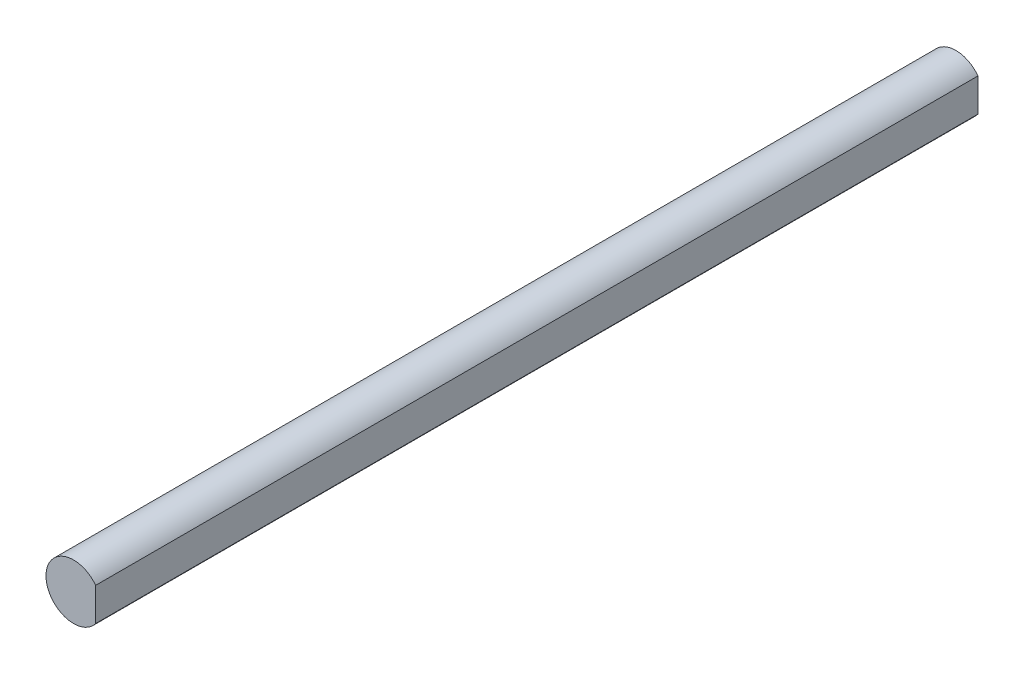
SolidWorks part; units mm, degrees
ref_plane "Plan de face" through (0, 0, 0) normal (0, 0, 1) x (1, 0, 0)
ref_plane "Plan de dessus" through (0, 0, 0) normal (0, 1, 0) x (1, 0, 0)
ref_plane "Plan de droite" through (0, 0, 0) normal (1, 0, 0) x (0, 0, -1)
sketch "Esquisse1" plane through (0, 0, 0) normal (0, 0, 1) x (1, 0, 0)
  circle A0 centre (0, 0) radius 3.175
  dimension "D1" = 6.35
extrude "Boss.-Extru.1" add sketch "Esquisse1" along normal blind 101.6
sketch "Esquisse2" plane through (0, 0, 101.6) normal (0, 0, 1) x (1, 0, 0)
  line L0 (2.54, 1.905) -> (2.54, -1.905)
  line L1 (-3.175, 0) -> (0, 0) construction
  circle A0 centre (0, 0) radius 3.175 construction
  arc A2 (2.54, -1.905) -> (2.54, 1.905) centre (0, 0) ccw
  point P4 (-3.175, 0)
  point P8 (0, 0)
  dimension "D1" = 5.715
extrude "Enlèv. mat.-Extru.1" cut sketch "Esquisse2" against normal through all
